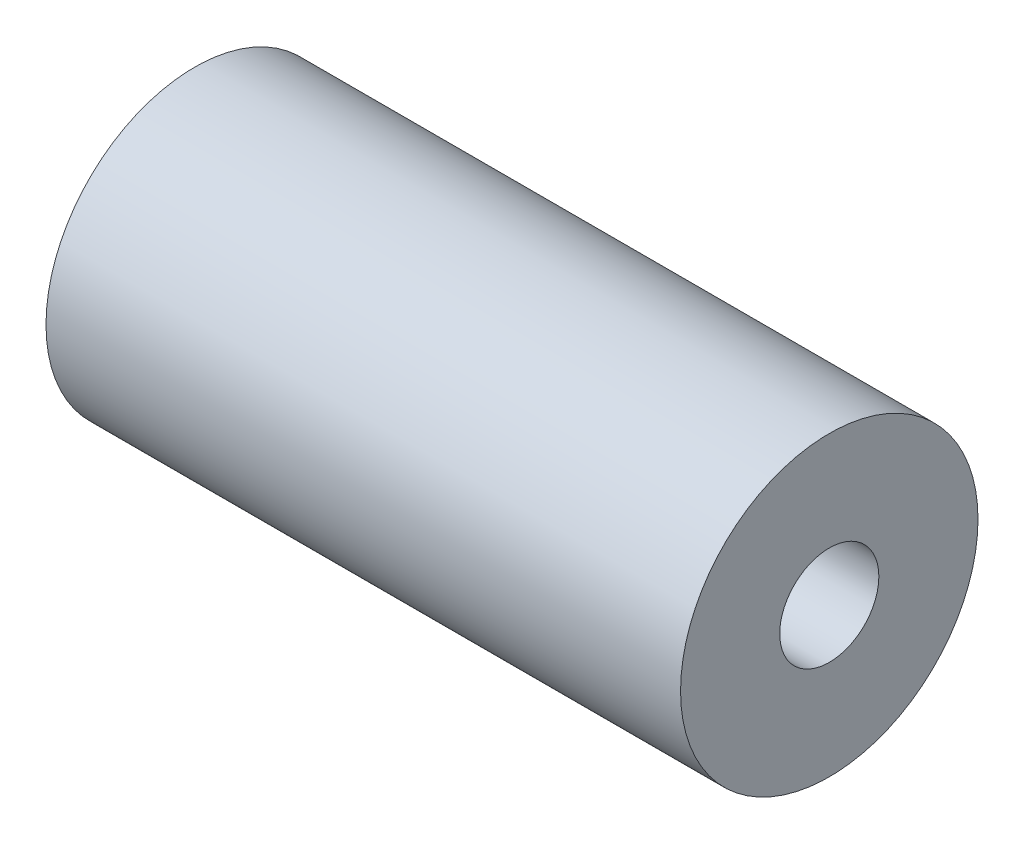
SolidWorks part; units mm, degrees
ref_plane "Plan de face" through (0, 0, 0) normal (0, 0, 1) x (1, 0, 0)
ref_plane "Plan de dessus" through (0, 0, 0) normal (0, 1, 0) x (1, 0, 0)
ref_plane "Plan de droite" through (0, 0, 0) normal (1, 0, 0) x (0, 0, -1)
sketch "Esquisse1" plane through (0, 0, 0) normal (0, 0, 1) x (1, 0, 0)
  line L1 (0, 0) -> (32, 0)
  line L2 (0, 0) -> (0, 7.5)
  line L3 (0, 7.5) -> (32, 7.5)
  line L4 (32, 0) -> (32, 7.5)
  dimension "D1" = 7.5
  dimension "D2" = 32
revolve "Révolution2" add sketch "Esquisse1" angle 360 about L3
sketch "Esquisse2" plane through (32, 0, 0) normal (1, 0, 0) x (0, 0, -1)
  circle A0 centre (0, 7.5) radius 2.5
  circle A1 centre (0, 7.5) radius 7.5 construction
  point P2 (0, 8.1449)
  point P3 (0, 7.2278)
  dimension "D1" = 5
  dimension "D2" = 0
extrude "Enlèv. mat.-Extru.1" cut sketch "Esquisse2" against normal blind 22
sketch "Esquisse4" plane through (0, 0, 0) normal (-1, 0, 0) x (0, 0, 1)
  circle A0 centre (0, 7.5) radius 4
  dimension "D1" = 8
extrude "Enlèv. mat.-Extru.2" cut sketch "Esquisse4" against normal blind 6
sketch "Esquisse10" plane through (0, 0, 0) normal (0, 1, 0) x (1, 0, 0)
  circle A0 centre (12.9949, 0) radius 0.7938
hole_wizard "Dégagement M1.41" positions "Esquisse3D4" profile "Esquisse15" hole size "M1.4" standard "ISO"
sketch3d "Esquisse3D4"
  point P0 (21.8948, 0.0225, -0.5803)
  point P5 (12.9949, 0, 0)
  point P8 (12.7888, 0.0051, -0.2767)
sketch "Esquisse15" plane through (21.8948, 0.0225, -0.5803) normal (1, 0, 0) x (0, 0.0774, -0.997)
  line L0 (0, 0) -> (0, 6.4807)
  line L1 (0, 6.4807) -> (0.8, 6)
  line L2 (0.8, 6) -> (0.8, 0)
  line L5 (0.8, 0) -> (0, 0)
  line L10 (0, 6.4807) -> (-0.8, 6) construction
  line L11 (0, -6.35) -> (0, 107.95) construction
  dimension "Diamètre du perçage" = 1.6
  dimension "Profondeur du perçage" = 6
  dimension "Angle de pointe" = 118
